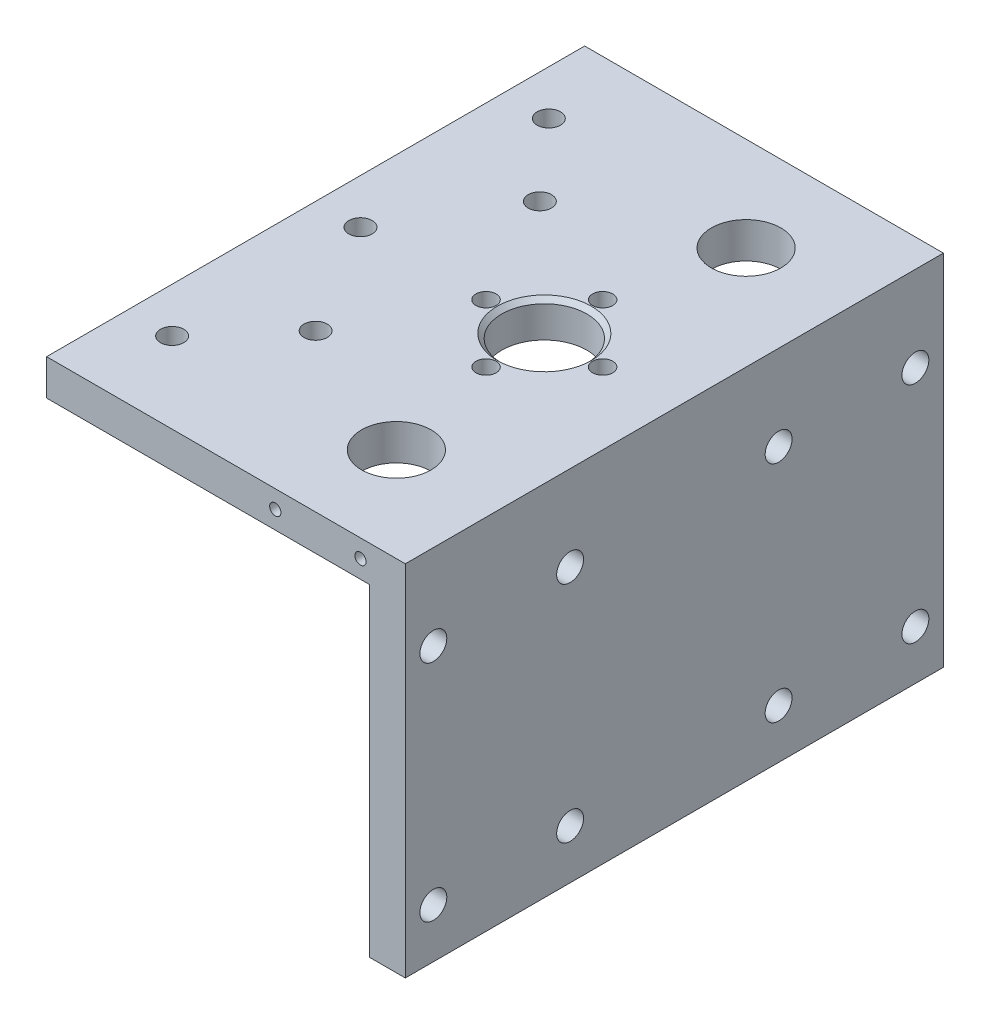
SolidWorks part; units mm, degrees
material "Lega 1060"
ref_plane "Piano frontale" through (0, 0, 0) normal (0, 0, 1) x (1, 0, 0)
ref_plane "Piano superiore" through (0, 0, 0) normal (0, 1, 0) x (1, 0, 0)
ref_plane "Piano destro" through (0, 0, 0) normal (1, 0, 0) x (0, 0, -1)
sketch "Schizzo1" plane through (0, 0, 0) normal (0, 0, 1) x (1, 0, 0)
  line L0 (0, 0) -> (-80, 0)
  line L1 (-80, 0) -> (-80, -8)
  line L2 (-80, -8) -> (-8, -8)
  line L3 (-8, -8) -> (-8, -80)
  line L4 (-8, -80) -> (0, -80)
  line L5 (0, -80) -> (0, 0)
  dimension "D1" = 80
  dimension "D2" = 80
  dimension "D3" = 8
  dimension "D4" = 8
extrude "Estrusione-Estrusione1" add sketch "Schizzo1" along normal blind 120
sketch "Schizzo12" plane through (0, 0, 0) normal (1, 0, 0) x (0, 0, -1)
  line L0 (0, -8) -> (-120, -8) construction
  line L1 (-21.5, 0) -> (-21.5, 40.839) construction
  line L5 (0, -80) -> (0, 0) construction
  line L6 (-120, -80) -> (-120, 0) construction
  line L7 (-120, 0) -> (0, 0) construction
  line L8 (-113.75, -19) -> (9.6992, -19) construction
  line L9 (-113.75, -69) -> (15.4001, -69) construction
  line L10 (-98.5, -47.4454) -> (-98.5, 40.839) construction
  circle A0 centre (-113.75, -19) radius 3
  circle A1 centre (-83.25, -19) radius 3
  circle A6 centre (-36.75, -19) radius 3
  circle A7 centre (-6.25, -19) radius 3
  circle A10 centre (-83.25, -69) radius 3
  circle A11 centre (-113.75, -69) radius 3
  circle A12 centre (-6.25, -69) radius 3
  circle A13 centre (-36.75, -69) radius 3
  dimension "D1" = 6
  dimension "D5" = 30.5
  dimension "D6" = 30.5
  dimension "D7" = 30.5
  dimension "D8" = 30.5
  dimension "D2" = 8
  dimension "D3" = 11
  dimension "D4" = 61
  dimension "D9" = 21.5
  dimension "D10" = 21.5
sketch "Schizzo6" plane through (0, 0, 0) normal (0, 1, 0) x (1, 0, 0)
  line L0 (-23, -0.5808) -> (-23, -110.5835) construction
  line L2 (0, 0) -> (-80, 0) construction
  line L3 (-32.5218, -60) -> (-8.0464, -60) construction
  line L6 (0, -120) -> (-80, -120) construction
  circle A0 centre (-23, -21) radius 7.75
  circle A1 centre (-23, -99) radius 7.75
  dimension "D2" = 15.5
  dimension "D1" = 15
  dimension "D3" = 21
  dimension "D4" = 39
extrude "Taglio-Estrusione2" cut sketch "Schizzo6" against normal up to next
sketch "Schizzo7" plane through (0, 0, 0) normal (0, 1, 0) x (1, 0, 0)
  line L0 (-83.5082, -60) -> (3.6289, -60) construction
  line L1 (0, -120) -> (-80, -120) construction
  line L2 (0, 0) -> (-80, 0) construction
  line L3 (-23, -21) -> (-23, -99) construction
  line L4 (0, -120) -> (0, 0) construction
  circle A0 centre (-29, -60) radius 9.5
  dimension "D1" = 19
  dimension "D3" = 29
extrude "Taglio-Estrusione3" cut sketch "Schizzo7" against normal up to next
hole_wizard "Foro per Vite M4-2" positions "Schizzo9" profile "Schizzo8" hole size "M4" standard "ISO" end condition through all
sketch "Schizzo9" plane through (0, 0, 0) normal (0, 1, 0) x (1, 0, 0)
  line L0 (-18.4657, -60) -> (-16, -60) construction
  line L2 (-29, -57.7684) -> (-29, -66.5063) construction
  circle A2 centre (-29, -60) radius 9.5 construction
  point P0 (-29, -47)
  point P2 (-42, -60)
  point P4 (-29, -73)
  point P8 (-16, -60)
  point P20 (-29, -60)
  dimension "D1" = 26
  dimension "D2" = 13
  dimension "D3" = 13
sketch "Schizzo8" plane through (-29, 0, 47) normal (1, 0, 0) x (0, 0, 1)
  line L0 (0, 0) -> (0, 80)
  line L1 (0, 80) -> (2.25, 80)
  line L2 (2.25, 80) -> (2.25, 0)
  line L5 (2.25, 0) -> (0, 0)
  line L11 (0, -6.35) -> (0, 107.95) construction
  dimension "Thru Hole Dia." = 4.5
  dimension "Thru Hole Depth" = 80
extrude "Taglio-Estrusione4" cut sketch "Schizzo12" against normal blind 10
sketch "Schizzo14" plane through (0, 0, 0) normal (0, 1, 0) x (1, 0, 0)
  line L0 (-70, 0) -> (-70, -120) construction
  line L1 (0, 0) -> (-80, 0) construction
  line L2 (0, -120) -> (-80, -120) construction
  line L3 (-80, -120) -> (-80, 0) construction
  line L4 (-55, 0) -> (-55, -120) construction
  line L5 (-23, -99) -> (-80, -99) construction
  line L6 (-80, -60) -> (0, -60) construction
  line L7 (0, -120) -> (0, 0) construction
  line L8 (-23, -21) -> (-80, -21) construction
  circle A0 centre (-70, -18) radius 2.6
  circle A1 centre (-70, -60) radius 2.6
  circle A2 centre (-70, -102) radius 2.6
  circle A3 centre (-55, -35) radius 2.6
  circle A4 centre (-55, -85) radius 2.6
  dimension "D3" = 5.2
  dimension "D4" = 5.2
  dimension "D5" = 5.2
  dimension "D6" = 5.2
  dimension "D7" = 5.2
  dimension "D1" = 10
  dimension "D2" = 25
  dimension "D8" = 35
  dimension "D9" = 35
  dimension "D10" = 25
  dimension "D11" = 42
  dimension "D12" = 15
extrude "Taglio-Estrusione5" cut sketch "Schizzo14" against normal blind 10
chamfer "Smusso2" distance 1 angle 45 1 edges at (-38.5, 0, 60)
sketch "Schizzo15" plane through (0, 0, 120) normal (0, 0, 1) x (1, 0, 0)
  line L0 (-80, -4) -> (0, -4) construction
  line L1 (-80, 0) -> (-80, -8) construction
  line L2 (0, -80) -> (0, 0) construction
  point P6 (-10, -4)
  point P7 (-29, -4)
  dimension "D1" = 10
  dimension "D2" = 19
hole_wizard "Foro filettato M3-1" positions "Schizzo17" profile "Schizzo16" tap size "M3" standard "ISO"
sketch "Schizzo17" plane through (0, 0, 120) normal (0, 0, 1) x (1, 0, 0)
  point P0 (-10, -4)
  point P3 (-29, -4)
sketch "Schizzo16" plane through (-10, -4, 120) normal (1, 0, 0) x (0, -1, 0)
  line L0 (0, 0) -> (0, 10.7511)
  line L1 (0, 10.7511) -> (1.25, 10)
  line L2 (1.25, 10) -> (1.25, 0)
  line L5 (1.25, 0) -> (0, 0)
  line L10 (0, 10.7511) -> (-1.25, 10) construction
  line L11 (0, -6.35) -> (0, 107.95) construction
  dimension "Tap Drill Dia." = 2.5
  dimension "Tap Drill Depth" = 10
  dimension "Drill Angle" = 118
cosmetic thread "Filettatura del foro1" parameters "D1"=8, "D2"=3
cosmetic thread "Filettatura del foro2" parameters "D1"=8, "D2"=3
